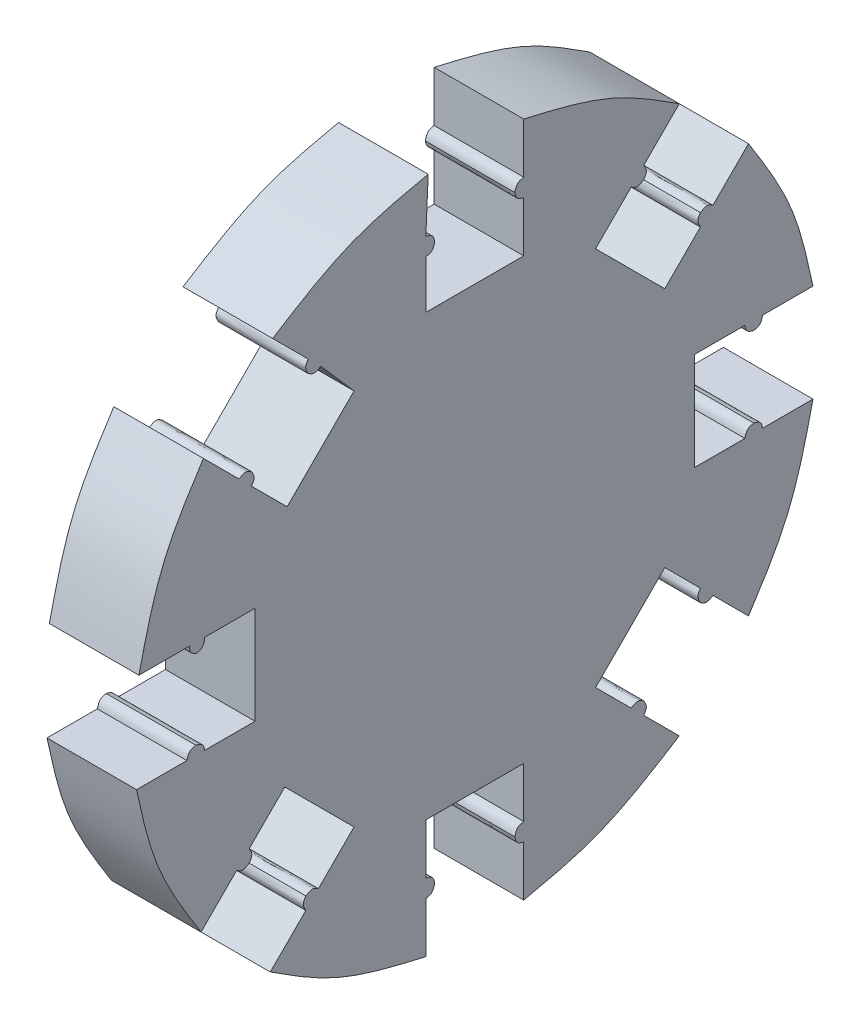
SolidWorks part; units mm, degrees
ref_plane "Alzado" through (0, 0, 0) normal (1, 0, 0) x (0, 1, 0)
ref_plane "Planta" through (0, 0, 0) normal (0, 0, 1) x (0, 1, 0)
ref_plane "Vista lateral" through (0, 0, 0) normal (0, 1, 0) x (-1, 0, 0)
sketch "Croquis1" plane through (0, 0, 0) normal (1, 0, 0) x (0, 1, 0)
  line L0 (7.2975, 4.9704) -> (8.3694, 6.0424)
  line L1 (10.3127, 1.3547) -> (8.7248, 1.4253)
  line L2 (8.1892, 1.4253) -> (6.7425, 1.4253)
  line L3 (6.7425, 1.4253) -> (6.7425, -1.5247)
  line L4 (6.7425, -1.5247) -> (8.2599, -1.5247)
  line L5 (8.7955, -1.5247) -> (10.3128, -1.5247)
  line L6 (8.3695, -6.2123) -> (7.2978, -5.1409)
  line L7 (6.919, -4.7621) -> (5.8459, -3.6889)
  line L8 (5.8459, -3.6889) -> (3.7599, -5.7749)
  line L9 (3.7599, -5.7749) -> (4.8331, -6.8481)
  line L10 (5.2118, -7.2268) -> (6.2832, -8.2981)
  line L11 (1.5957, -10.2409) -> (1.5957, -8.7247)
  line L12 (1.5957, -8.1891) -> (1.5957, -6.6714)
  line L13 (1.5957, -6.6714) -> (-1.3543, -6.6714)
  line L14 (-1.3543, -6.6714) -> (-1.3543, -8.1891)
  line L15 (-1.3543, -8.7247) -> (-1.3543, -10.2416)
  line L16 (-6.0421, -8.2984) -> (-4.9704, -7.2268)
  line L17 (-4.5918, -6.8481) -> (-3.5186, -5.7749)
  line L18 (-3.5186, -5.7749) -> (-5.6046, -3.6889)
  line L19 (-5.6046, -3.6889) -> (-6.6777, -4.7621)
  line L20 (-7.0565, -5.1409) -> (-8.128, -6.2121)
  line L21 (-10.0708, -1.5247) -> (-8.5542, -1.5247)
  line L22 (-8.0186, -1.5247) -> (-6.5011, -1.5247)
  line L23 (-6.5011, -1.5247) -> (-6.5011, 1.4253)
  line L24 (-6.5011, 1.4253) -> (-8.0186, 1.4253)
  line L25 (-8.5542, 1.4253) -> (-10.0715, 1.4253)
  line L26 (-8.1282, 6.113) -> (-7.0562, 5.0411)
  line L27 (-6.6775, 4.6625) -> (-5.6046, 3.5896)
  line L28 (-5.6046, 3.5896) -> (-3.5186, 5.6755)
  line L29 (-3.5186, 5.6755) -> (-4.5914, 6.7483)
  line L30 (-4.9701, 7.1272) -> (-6.0419, 8.1988)
  line L31 (-1.3543, 10.1416) -> (-1.3543, 8.6246)
  line L32 (-1.3543, 8.0891) -> (-1.3543, 6.5721)
  line L33 (-1.3543, 6.5721) -> (1.5957, 6.5721)
  line L34 (1.5957, 6.5721) -> (1.5957, 8.0891)
  line L35 (1.5957, 8.554) -> (1.5957, 10.0709)
  line L36 (6.2832, 8.1281) -> (5.2115, 7.0564)
  line L37 (4.8328, 6.6776) -> (3.7599, 5.6048)
  line L38 (3.7599, 5.6048) -> (5.7752, 3.5896)
  line L39 (5.7752, 3.5896) -> (6.9188, 4.5918)
  spline S0 degree 3 poles (6.9188, 4.5918) (6.877, 4.6638) (6.8018, 4.7935) (6.8829, 4.9159) (6.919, 4.9703) knots 0 0 0 0 0.555583 1 1 1 1
  spline S1 degree 3 poles (6.919, 4.9703) (6.991, 5.0121) (7.1206, 5.0874) (7.2431, 5.0064) (7.2975, 4.9704) knots 0 0 0 0 0.555689 1 1 1 1
  spline S2 degree 3 poles (8.3694, 6.0424) (8.8756, 5.2346) (9.7883, 3.778) (10.1511, 2.1015) (10.3127, 1.3547) knots 0 0 0 0 0.554563 1 1 1 1
  spline S3 degree 3 poles (8.7248, 1.4253) (8.7034, 1.3444) (8.665, 1.1994) (8.521, 1.1702) (8.457, 1.1572) knots 0 0 0 0 0.555657 1 1 1 1
  spline S4 degree 3 poles (8.457, 1.1572) (8.3764, 1.1785) (8.2314, 1.217) (8.2022, 1.361) (8.1892, 1.4253) knots 0 0 0 0 0.555664 1 1 1 1
  spline S5 degree 3 poles (8.2599, -1.5247) (8.2813, -1.4442) (8.3198, -1.2994) (8.4637, -1.2702) (8.5277, -1.2573) knots 0 0 0 0 0.555596 1 1 1 1
  spline S6 degree 3 poles (8.5277, -1.2573) (8.6082, -1.2786) (8.7531, -1.3169) (8.7824, -1.4608) (8.7955, -1.5247) knots 0 0 0 0 0.555719 1 1 1 1
  spline S7 degree 3 poles (10.3128, -1.5247) (10.0938, -2.4703) (9.7059, -4.1451) (8.7749, -5.5852) (8.3695, -6.2123) knots 0 0 0 0 0.564581 1 1 1 1
  spline S8 degree 3 poles (7.2978, -5.1409) (7.2256, -5.1828) (7.0959, -5.2582) (6.9734, -5.177) (6.919, -5.1409) knots 0 0 0 0 0.55566 1 1 1 1
  spline S9 degree 3 poles (6.919, -5.1409) (6.8771, -5.0689) (6.8017, -4.9392) (6.8829, -4.8167) (6.919, -4.7621) knots 0 0 0 0 0.555577 1 1 1 1
  spline S10 degree 3 poles (4.8331, -6.8481) (4.9052, -6.8063) (5.0348, -6.731) (5.1573, -6.8122) (5.2117, -6.8482) knots 0 0 0 0 0.555628 1 1 1 1
  spline S11 degree 3 poles (5.2117, -6.8482) (5.2536, -6.9203) (5.329, -7.0499) (5.2478, -7.1724) (5.2118, -7.2268) knots 0 0 0 0 0.555759 1 1 1 1
  spline S12 degree 3 poles (6.2832, -8.2981) (5.4754, -8.8041) (4.0187, -9.7165) (2.3424, -10.0793) (1.5957, -10.2409) knots 0 0 0 0 0.554569 1 1 1 1
  spline S13 degree 3 poles (1.5957, -8.7247) (1.5151, -8.7034) (1.3701, -8.6649) (1.3409, -8.5209) (1.3279, -8.4569) knots 0 0 0 0 0.555707 1 1 1 1
  spline S14 degree 3 poles (1.3279, -8.4569) (1.3493, -8.3763) (1.3877, -8.2313) (1.5317, -8.2021) (1.5957, -8.1891) knots 0 0 0 0 0.555589 1 1 1 1
  spline S15 degree 3 poles (-1.3543, -8.1891) (-1.2737, -8.2105) (-1.1287, -8.2489) (-1.0995, -8.3929) (-1.0865, -8.4569) knots 0 0 0 0 0.555651 1 1 1 1
  spline S16 degree 3 poles (-1.0865, -8.4569) (-1.1079, -8.5375) (-1.1463, -8.6825) (-1.2903, -8.7117) (-1.3543, -8.7247) knots 0 0 0 0 0.55566 1 1 1 1
  spline S17 degree 3 poles (-1.3543, -10.2416) (-2.2999, -10.0226) (-3.9748, -9.6347) (-5.415, -8.7038) (-6.0421, -8.2984) knots 0 0 0 0 0.564577 1 1 1 1
  spline S18 degree 3 poles (-4.9704, -7.2268) (-5.0123, -7.1547) (-5.0876, -7.0251) (-5.0064, -6.9026) (-4.9703, -6.8482) knots 0 0 0 0 0.555537 1 1 1 1
  spline S19 degree 3 poles (-4.9703, -6.8482) (-4.8983, -6.8064) (-4.7687, -6.731) (-4.6462, -6.8121) (-4.5918, -6.8481) knots 0 0 0 0 0.555697 1 1 1 1
  spline S20 degree 3 poles (-6.6777, -4.7621) (-6.6358, -4.8343) (-6.5604, -4.964) (-6.6416, -5.0865) (-6.6777, -5.1409) knots 0 0 0 0 0.555721 1 1 1 1
  spline S21 degree 3 poles (-6.6777, -5.1409) (-6.7498, -5.1828) (-6.8795, -5.2582) (-7.0019, -5.177) (-7.0565, -5.1409) knots 0 0 0 0 0.555668 1 1 1 1
  spline S22 degree 3 poles (-8.128, -6.2121) (-8.634, -5.4043) (-9.5464, -3.9476) (-9.9092, -2.2713) (-10.0708, -1.5247) knots 0 0 0 0 0.554568 1 1 1 1
  spline S23 degree 3 poles (-8.5542, -1.5247) (-8.5328, -1.4442) (-8.4943, -1.2993) (-8.3503, -1.2702) (-8.2864, -1.2572) knots 0 0 0 0 0.555529 1 1 1 1
  spline S24 degree 3 poles (-8.2864, -1.2572) (-8.2058, -1.2786) (-8.0609, -1.3169) (-8.0316, -1.4608) (-8.0186, -1.5247) knots 0 0 0 0 0.555715 1 1 1 1
  spline S25 degree 3 poles (-8.0186, 1.4253) (-8.0399, 1.3444) (-8.0784, 1.1994) (-8.2224, 1.1702) (-8.2864, 1.1572) knots 0 0 0 0 0.555663 1 1 1 1
  spline S26 degree 3 poles (-8.2864, 1.1572) (-8.367, 1.1785) (-8.512, 1.2169) (-8.5412, 1.361) (-8.5542, 1.4253) knots 0 0 0 0 0.55571 1 1 1 1
  spline S27 degree 3 poles (-10.0715, 1.4253) (-9.8525, 2.3709) (-9.4646, 4.0458) (-8.5336, 5.486) (-8.1282, 6.113) knots 0 0 0 0 0.564575 1 1 1 1
  spline S28 degree 3 poles (-7.0562, 5.0411) (-6.9841, 5.0829) (-6.8545, 5.1581) (-6.7321, 5.077) (-6.6777, 5.0409) knots 0 0 0 0 0.555662 1 1 1 1
  spline S29 degree 3 poles (-6.6777, 5.0409) (-6.6358, 4.9689) (-6.5605, 4.8393) (-6.6415, 4.7169) (-6.6775, 4.6625) knots 0 0 0 0 0.55574 1 1 1 1
  spline S30 degree 3 poles (-4.5914, 6.7483) (-4.6637, 6.7064) (-4.7934, 6.6311) (-4.9159, 6.7123) (-4.9703, 6.7483) knots 0 0 0 0 0.555672 1 1 1 1
  spline S31 degree 3 poles (-4.9703, 6.7483) (-5.0122, 6.8204) (-5.0876, 6.9501) (-5.0064, 7.0725) (-4.9701, 7.1272) knots 0 0 0 0 0.555581 1 1 1 1
  spline S32 degree 3 poles (-6.0419, 8.1988) (-5.234, 8.7048) (-3.7773, 9.6172) (-2.101, 9.98) (-1.3543, 10.1416) knots 0 0 0 0 0.55456 1 1 1 1
  spline S33 degree 3 poles (-1.3543, 8.6246) (-1.2737, 8.6033) (-1.1287, 8.5649) (-1.0995, 8.4209) (-1.0865, 8.3569) knots 0 0 0 0 0.555651 1 1 1 1
  spline S34 degree 3 poles (-1.0865, 8.3569) (-1.1079, 8.2763) (-1.1463, 8.1313) (-1.2903, 8.1021) (-1.3543, 8.0891) knots 0 0 0 0 0.55566 1 1 1 1
  spline S35 degree 3 poles (1.5957, 8.0891) (1.5131, 8.1003) (1.3644, 8.1203) (1.3175, 8.2596) (1.2967, 8.3215) knots 0 0 0 0 0.555707 1 1 1 1
  spline S36 degree 3 poles (1.2967, 8.3215) (1.3279, 8.3988) (1.384, 8.538) (1.5306, 8.549) (1.5957, 8.554) knots 0 0 0 0 0.555589 1 1 1 1
  spline S37 degree 3 poles (1.5957, 10.0709) (2.5412, 9.852) (4.216, 9.4641) (5.6561, 8.5334) (6.2832, 8.1281) knots 0 0 0 0 0.564577 1 1 1 1
  spline S38 degree 3 poles (5.2115, 7.0564) (5.2536, 6.9841) (5.329, 6.8544) (5.2477, 6.732) (5.2117, 6.6776) knots 0 0 0 0 0.555719 1 1 1 1
  spline S39 degree 3 poles (5.2117, 6.6776) (5.1396, 6.6357) (5.0099, 6.5603) (4.8874, 6.6415) (4.8328, 6.6776) knots 0 0 0 0 0.555672 1 1 1 1
  dimension "D1" = 2.95
  dimension "D2" = 2.95
  dimension "D3" = 2.95
  dimension "D4" = 2.95
  dimension "D5" = 2.95
  dimension "D6" = 2.95
  dimension "D7" = 2.95
  dimension "D8" = 2.95
extrude "Saliente-Extruir1" add sketch "Croquis1" along normal blind 2.7
